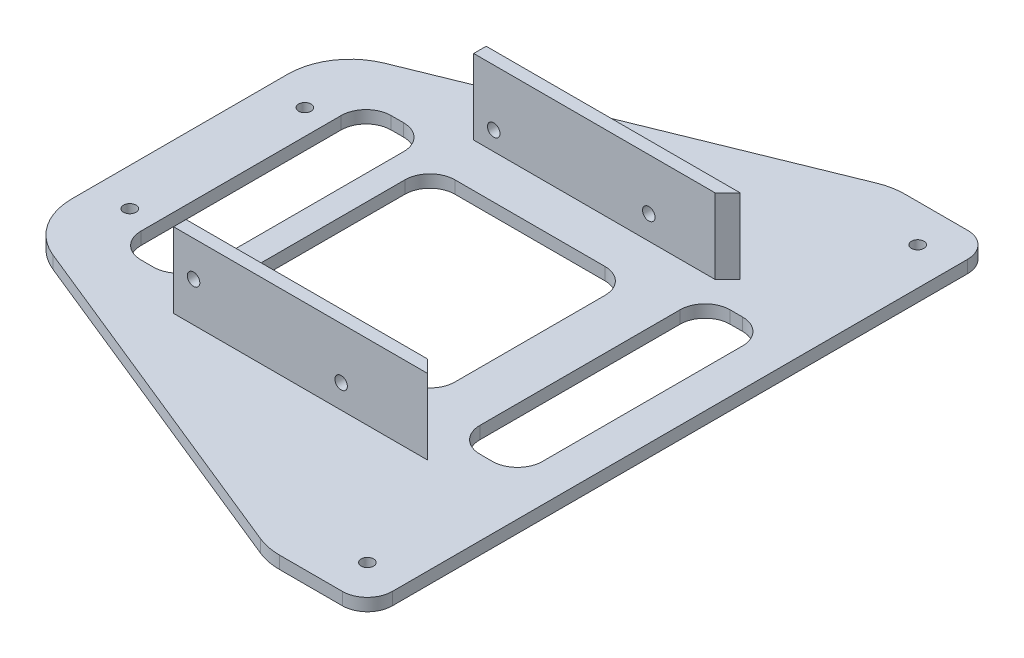
SolidWorks part; units mm, degrees
ref_plane "Plano frontal" through (0, 0, 0) normal (0, 0, 1) x (1, 0, 0)
ref_plane "Plano superior" through (0, 0, 0) normal (0, 1, 0) x (1, 0, 0)
ref_plane "Plano direito" through (0, 0, 0) normal (1, 0, 0) x (0, 0, -1)
sketch "Esboço1" plane through (0, 0, 0) normal (0, 1, 0) x (1, 0, 0)
  line L0 (91.7241, -57.7155) -> (61.7241, -57.7155) construction
  line L1 (66.6084, -57.7155) -> (91.7241, -57.7155)
  line L2 (-98.2759, 24.1125) -> (-98.2759, 110.4565)
  line L3 (66.6084, 192.2845) -> (91.7241, 192.2845)
  line L4 (101.7241, -47.7155) -> (101.7241, 182.2845)
  line L5 (61.7241, -57.7155) -> (61.7241, 192.2845) construction
  line L6 (-98.2759, 67.2845) -> (-98.2759, 7.2845) construction
  line L7 (-98.2759, 7.2845) -> (-98.2759, 127.2845) construction
  line L8 (-82.6853, 0.9508) -> (57.199, -55.8772)
  line L9 (-82.6853, 133.6182) -> (57.199, 190.4461)
  arc A2 (101.7241, 182.2845) -> (91.7241, 192.2845) centre (91.7241, 182.2845) ccw
  arc A3 (91.7241, -57.7155) -> (101.7241, -47.7155) centre (91.7241, -47.7155) ccw
  arc A4 (57.199, 190.4461) -> (66.6084, 192.2845) centre (66.6084, 167.2845) cw
  arc A5 (-82.6853, 133.6182) -> (-98.2759, 110.4565) centre (-73.2759, 110.4565) ccw
  arc A6 (57.199, -55.8772) -> (66.6084, -57.7155) centre (66.6084, -32.7155) ccw
  arc A7 (-98.2759, 24.1125) -> (-82.6853, 0.9508) centre (-73.2759, 24.1125) ccw
  point P6 (-98.2759, -57.7155)
  point P9 (-98.2759, 192.2845)
  point P12 (101.7241, 192.2845)
  dimension "D3" = 25
  dimension "D1" = 200
  dimension "D2" = 250
extrude "Ressalto-extrusão1" add sketch "Esboço1" along normal blind 5
sketch "Esboço2" plane through (0, 5, 0) normal (0, 1, 0) x (1, 0, 0)
  line L0 (91.7241, 192.2845) -> (66.6084, 192.2845) construction
  line L1 (-98.2759, 110.4565) -> (-98.2759, 24.1125) construction
  line L2 (-98.2759, 67.2845) -> (101.7241, 67.2845) construction
  line L3 (101.7241, -47.7155) -> (101.7241, 182.2845) construction
  line L4 (79.1663, 192.2845) -> (79.1663, -57.7155) construction
  line L5 (66.6084, -57.7155) -> (91.7241, -57.7155) construction
  line L6 (-98.2759, 67.2845) -> (-98.2759, 87.2845) construction
  line L7 (31.7241, 107.2845) -> (-28.2759, 107.2845)
  line L8 (41.7241, 97.2845) -> (41.7241, 37.2845)
  line L9 (31.7241, 27.2845) -> (-28.2759, 27.2845)
  line L10 (-38.2759, 97.2845) -> (-38.2759, 37.2845)
  line L11 (41.7241, 107.2845) -> (-38.2759, 27.2845) construction
  line L12 (41.7241, 27.2845) -> (-38.2759, 107.2845) construction
  line L13 (-98.2759, 110.4565) -> (-98.2759, 24.1125) construction
  line L14 (-98.2759, 47.2845) -> (-83.2759, 47.2845) construction
  line L15 (-83.2759, 47.2845) -> (-83.2759, 32.2845) construction
  line L16 (-98.2759, 87.2845) -> (-83.2759, 87.2845) construction
  line L17 (-83.2759, 87.2845) -> (-83.2759, 102.2845) construction
  circle A0 centre (-83.2759, 102.2845) radius 2.5
  circle A1 centre (86.7241, 177.2845) radius 2.5
  circle A2 centre (86.7241, -42.7155) radius 2.5
  circle A3 centre (-83.2759, 32.2845) radius 2.5
  arc A4 (41.7241, 97.2845) -> (31.7241, 107.2845) centre (31.7241, 97.2845) ccw
  arc A5 (-38.2759, 97.2845) -> (-28.2759, 107.2845) centre (-28.2759, 97.2845) cw
  arc A6 (-38.2759, 37.2845) -> (-28.2759, 27.2845) centre (-28.2759, 37.2845) ccw
  arc A7 (31.7241, 27.2845) -> (41.7241, 37.2845) centre (31.7241, 37.2845) ccw
  point P20 (1.7241, 67.2845)
  dimension "D1" = 15
  dimension "D2" = 10
  dimension "D4" = 80
  dimension "D5" = 80
extrude "Corte-extrusão1" cut sketch "Esboço2" against normal through all
sketch "Esboço4" plane through (0, 5, 0) normal (0, 1, 0) x (1, 0, 0)
  line L0 (-38.2759, 124.7845) -> (-38.2759, 9.7845) construction
  line L1 (58.2241, 9.7845) -> (-38.2759, 9.7845)
  line L3 (58.2241, 124.7845) -> (-38.2759, 124.7845)
  line L5 (91.7241, 192.2845) -> (66.6084, 192.2845) construction
  line L7 (58.2241, 9.7845) -> (63.2241, 4.7845)
  line L8 (63.2241, 4.7845) -> (-38.2759, 4.7845)
  line L10 (63.2241, 129.7845) -> (-38.2759, 129.7845)
  line L12 (58.2241, 124.7845) -> (63.2241, 129.7845)
  line L14 (-38.2759, 4.7845) -> (-38.2759, 9.7845)
  line L15 (-59.7759, 4.7845) -> (-59.7759, 129.7845) construction
  line L16 (-54.7759, 9.7845) -> (-54.7759, 124.7845) construction
  line L17 (63.2241, 4.7845) -> (63.2241, 129.7845) construction
  line L18 (58.2241, 9.7845) -> (58.2241, 124.7845) construction
  line L19 (63.2241, 4.7845) -> (-59.7759, 4.7845) construction
  line L20 (58.2241, 9.7845) -> (-54.7759, 9.7845) construction
  line L21 (-38.2759, 124.7845) -> (-38.2759, 129.7845)
  line L22 (58.2241, 124.7845) -> (-54.7759, 124.7845) construction
  line L23 (63.2241, 129.7845) -> (-59.7759, 129.7845) construction
  dimension "D5" = 62.5
  dimension "D3" = 5
extrude "Ressalto-extrusão2" add sketch "Esboço4" along normal blind 30
sketch "Esboço5" plane through (0, 0, -4.7845) normal (0, 0, 1) x (1, 0, 0)
  line L2 (-30.2759, 20.8362) -> (-30.2759, 10.3362) construction
  line L3 (63.2241, 14.5) -> (28.7241, 14.5) construction
  line L4 (63.2241, 35) -> (63.2241, 5) construction
  line L5 (28.7241, 14.5) -> (28.7241, 5) construction
  line L6 (-38.2759, 5) -> (63.2241, 5) construction
  circle A0 centre (-30.2759, 20.8362) radius 2.5
  circle A1 centre (28.7241, 14.5) radius 2.5
  dimension "D3" = 9.5
  dimension "D2" = 10.5
extrude "Corte-extrusão2" cut sketch "Esboço5" against normal blind 5
sketch "Esboço6" plane through (0, 0, -129.7845) normal (0, 0, -1) x (-1, 0, 0)
  line L0 (-31.7241, 5) -> (-31.7241, 14.5) construction
  line L1 (-63.2241, 5) -> (38.2759, 5) construction
  line L2 (-31.7241, 14.5) -> (-63.2241, 14.5) construction
  line L3 (-63.2241, 35) -> (-63.2241, 5) construction
  line L4 (30.2759, 5) -> (30.2759, 12.5) construction
  circle A0 centre (-31.7241, 14.5) radius 2.5
  circle A1 centre (30.2759, 12.5) radius 2.5
  dimension "D3" = 9.5
  dimension "D1" = 31.5
  dimension "D4" = 7.5
extrude "Corte-extrusão3" cut sketch "Esboço6" against normal blind 5
sketch "Esboço7" plane through (0, 5, 0) normal (0, 1, 0) x (1, 0, 0)
  line L0 (86.7241, 67.2845) -> (101.7241, 67.2845) construction
  line L1 (76.7241, 117.2845) -> (71.7241, 117.2845)
  line L2 (86.7241, 107.2845) -> (86.7241, 27.2845)
  line L3 (76.7241, 17.2845) -> (71.7241, 17.2845)
  line L4 (61.7241, 107.2845) -> (61.7241, 27.2845)
  line L5 (101.7241, -47.7155) -> (101.7241, 182.2845) construction
  line L6 (-73.2894, 116.7845) -> (-73.2894, 192.2845) construction
  line L7 (91.7241, 192.2845) -> (66.6084, 192.2845) construction
  line L9 (-58.2894, 116.7845) -> (-63.2894, 116.7845)
  line L10 (-48.2894, 106.7845) -> (-48.2894, 26.7845)
  line L11 (-58.2894, 16.7845) -> (-63.2894, 16.7845)
  line L12 (-73.2894, 106.7845) -> (-73.2894, 26.7845)
  arc A0 (71.7241, 17.2845) -> (61.7241, 27.2845) centre (71.7241, 27.2845) cw
  arc A1 (76.7241, 17.2845) -> (86.7241, 27.2845) centre (76.7241, 27.2845) ccw
  arc A2 (71.7241, 117.2845) -> (61.7241, 107.2845) centre (71.7241, 107.2845) ccw
  arc A3 (86.7241, 107.2845) -> (76.7241, 117.2845) centre (76.7241, 107.2845) ccw
  arc A4 (-58.2894, 16.7845) -> (-48.2894, 26.7845) centre (-58.2894, 26.7845) ccw
  arc A5 (-73.2894, 26.7845) -> (-63.2894, 16.7845) centre (-63.2894, 26.7845) ccw
  arc A6 (-73.2894, 106.7845) -> (-63.2894, 116.7845) centre (-63.2894, 106.7845) cw
  arc A7 (-48.2894, 106.7845) -> (-58.2894, 116.7845) centre (-58.2894, 106.7845) ccw
  point P12 (61.7241, 17.2845)
  point P15 (86.7241, 17.2845)
  point P20 (86.7241, 117.2845)
  point P28 (-48.2894, 16.7845)
  point P31 (-73.2894, 16.7845)
  dimension "D5" = 10
  dimension "D9" = 10
  dimension "D1" = 15
  dimension "D2" = 75
  dimension "D3" = 100
  dimension "D4" = 25
  dimension "D6" = 25
  dimension "D7" = 100
  dimension "D8" = 75.5
extrude "Corte-extrusão4" cut sketch "Esboço7" against normal blind 10
